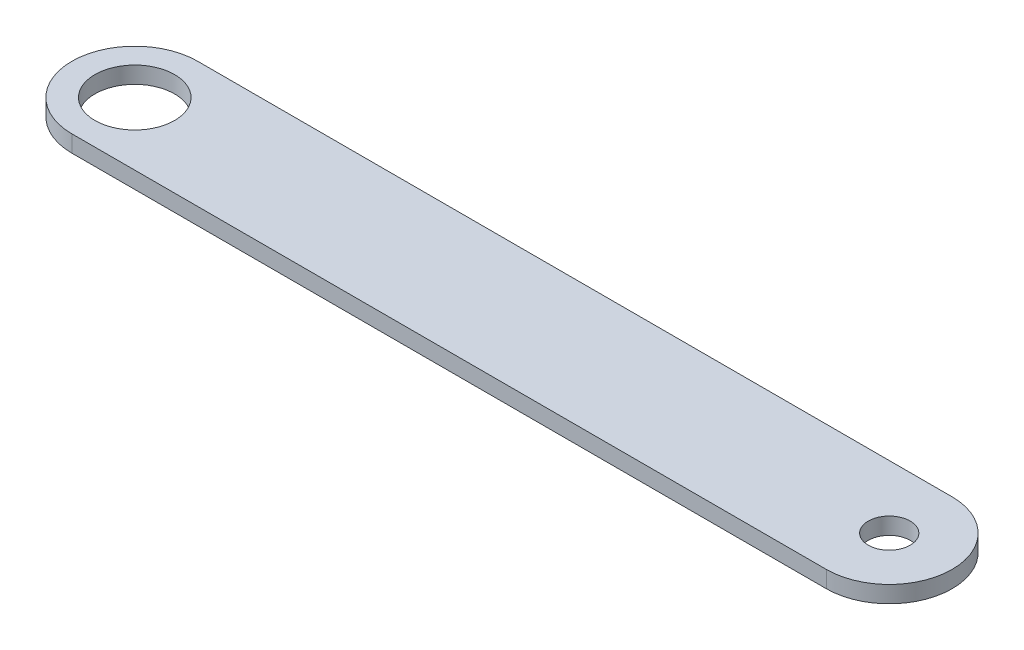
SolidWorks part; units mm, degrees
ref_plane "前视基准面" through (0, 0, 0) normal (0, 0, 1) x (1, 0, 0)
ref_plane "上视基准面" through (0, 0, 0) normal (0, 1, 0) x (1, 0, 0)
ref_plane "右视基准面" through (0, 0, 0) normal (1, 0, 0) x (0, 0, -1)
other "Configuration Table"
sketch "草图1" plane through (0, 0, 0) normal (0, 1, 0) x (1, 0, 0)
  line L0 (0, 0) -> (-180, 0) construction
  line L1 (0, -15) -> (-180, -15)
  line L2 (0, 15) -> (-180, 15)
  arc A0 (0, -15) -> (0, 15) centre (0, 0) ccw
  arc A1 (-180, 15) -> (-180, -15) centre (-180, 0) ccw
  point P3 (-90, 0)
  dimension "D1" = 15
  dimension "D2" = 180
extrude "凸台-拉伸1" add sketch "草图1" along normal blind 4
sketch "草图2" plane through (0, 4, 0) normal (0, 1, 0) x (1, 0, 0)
  circle A0 centre (0, 0) radius 5
  circle A1 centre (-180, 0) radius 9.5
  arc A2 (-180, 15) -> (-180, -15) centre (-180, 0) ccw construction
  dimension "D1" = 19
  dimension "D2" = 10
extrude "切除-拉伸1" cut sketch "草图2" against normal through all
